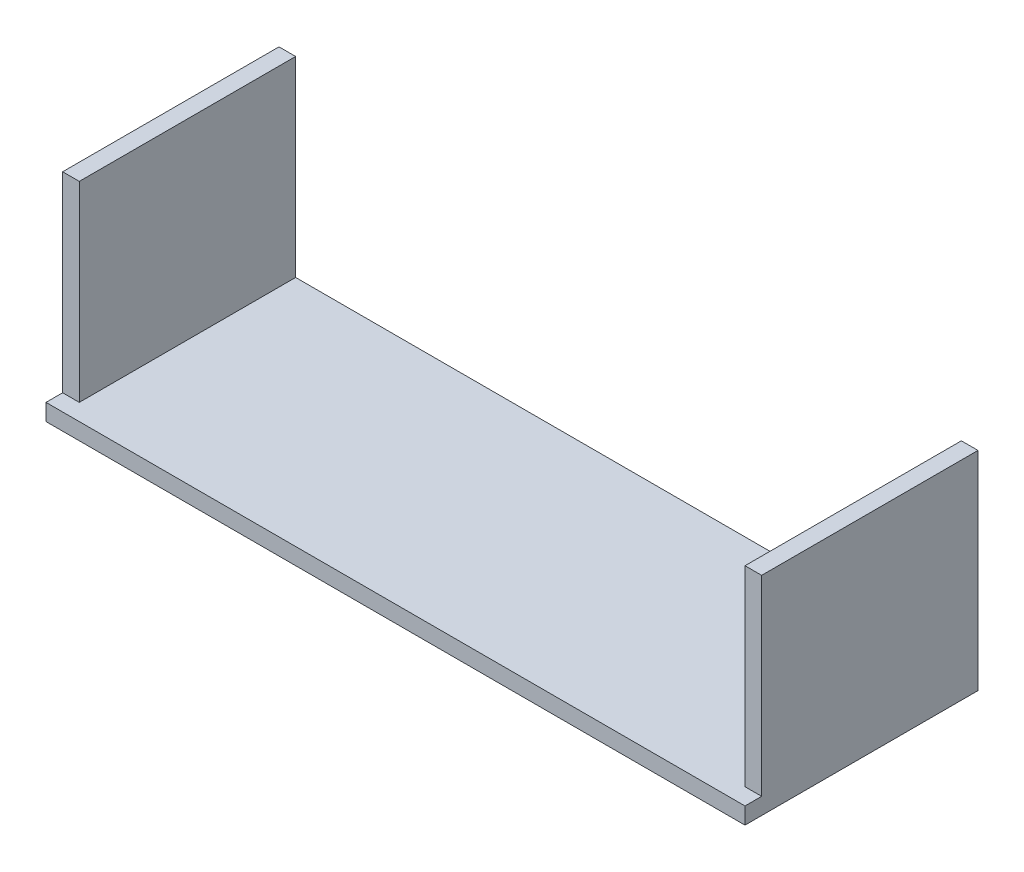
SolidWorks part; units mm, degrees
ref_plane "前视基准面" through (0, 0, 0) normal (0, 0, 1) x (1, 0, 0)
ref_plane "上视基准面" through (0, 0, 0) normal (0, 1, 0) x (1, 0, 0)
ref_plane "右视基准面" through (0, 0, 0) normal (1, 0, 0) x (0, 0, -1)
sketch "Sketch1" plane through (0, 0, 0) normal (0, 1, 0) x (1, 0, 0)
  line L1 (0, 0) -> (533.4, 0)
  line L2 (0, 0) -> (0, -177.8)
  line L3 (0, -177.8) -> (533.4, -177.8)
  line L4 (533.4, 0) -> (533.4, -177.8)
  dimension "D1" = 533.4
  dimension "D2" = 177.8
extrude "Extrude1" add sketch "Sketch1" along normal blind 12.7 contours L1 L4 L3 L2
sketch "Sketch2" plane through (0, 12.7, 0) normal (0, 1, 0) x (1, 0, 0)
  line L0 (0, -177.8) -> (533.4, -177.8) construction
  line L1 (0, 0) -> (12.7, 0)
  line L2 (0, 0) -> (0, -177.8)
  line L3 (0, -177.8) -> (12.7, -177.8)
  line L4 (12.7, 0) -> (12.7, -177.8)
  line L5 (0, 0) -> (533.4, 0) construction
  line L6 (520.7, 0) -> (533.4, 0)
  line L7 (520.7, 0) -> (520.7, -177.8)
  line L8 (520.7, -177.8) -> (533.4, -177.8)
  line L9 (533.4, 0) -> (533.4, -177.8)
  dimension "D1" = 12.7
  dimension "D2" = 12.7
extrude "Extrude2" add sketch "Sketch2" along normal blind 146.05
sketch "Sketch3" plane through (0, 0, 0) normal (-1, 0, 0) x (0, 0, 1)
  line L0 (165.1, 12.7) -> (177.8, 12.7)
  line L2 (177.8, 12.7) -> (177.8, 158.75)
  line L3 (0, 158.75) -> (177.8, 158.75) construction
  line L4 (177.8, 158.75) -> (165.1, 158.75)
  line L5 (165.1, 158.75) -> (165.1, 12.7)
  line L6 (177.8, 158.75) -> (177.8, 0) construction
  dimension "D2" = 12.7
extrude "Extrude3" cut sketch "Sketch3" against normal blind 614.172
sketch "Sketch4" plane through (0, 0, 0) normal (0, -1, 0) x (1, 0, 0)
  line L0 (0, 0) -> (533.4, 0) construction
  line L1 (396.24, 139.7) -> (322.58, 139.7)
  line L2 (396.24, 139.7) -> (396.24, 30.48)
  line L3 (396.24, 30.48) -> (322.58, 30.48)
  line L4 (322.58, 139.7) -> (322.58, 30.48)
  line L5 (0, 177.8) -> (533.4, 177.8) construction
  line L6 (0, 0) -> (0, 177.8) construction
  dimension "D1" = 30.48
  dimension "D2" = 38.1
  dimension "D3" = 322.58
  dimension "D4" = 396.24
extrude "Cut-Extrude1" cut sketch "Sketch4" against normal blind 2.54
sketch "Sketch5" plane through (0, 2.54, 0) normal (0, -1, 0) x (1, 0, 0)
  line L0 (0, 0) -> (0, 177.8) construction
  text T0 "MyRIO" height in points 48
  point P1 (0, 0)
  point P2 (0, 0)
  dimension "D1" = 335.28
extrude "Cut-Extrude2" cut sketch "Sketch5" against normal blind 5.08
